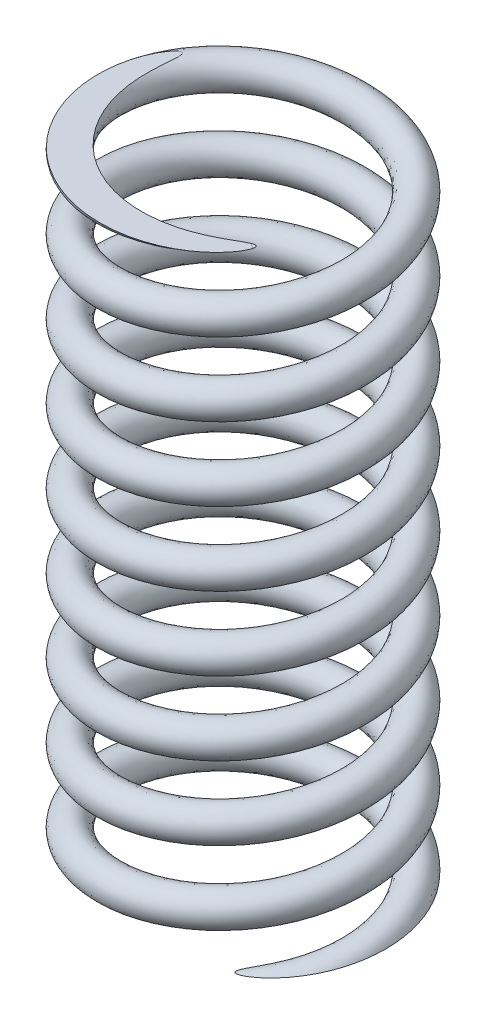
SolidWorks part; units mm, degrees
ref_plane "Front Plane" through (0, 0, 0) normal (0, 0, 1) x (1, 0, 0)
ref_plane "Top Plane" through (0, 0, 0) normal (0, 1, 0) x (1, 0, 0)
ref_plane "Right Plane" through (0, 0, 0) normal (1, 0, 0) x (0, 0, -1)
sketch "Sketch1" plane through (0, 0, 0) normal (0, 1, 0) x (1, 0, 0)
  circle A0 centre (0, 0) radius 14.3
  point P3 (0, 0)
curve "Helix/Spiral3" pitch 8.5703 height 83.56 turns 9.75
sketch "Sketch3" plane through (0, 0, 0) normal (0, 0, 1) x (1, 0, 0)
  circle A0 centre (-14.3, 0) radius 1.95
sweep "Sweep2" add profiles "Sketch3" path "Helix/Spiral3"
ref_plane "Plane4" through (0, 78.5, 0) normal (0, 1, 0) x (1, 0, 0)
other "SurfaceCut2"
ref_plane "Plane6" through (0, 5.1, 0) normal (0, 1, 0) x (1, 0, 0)
other "SurfaceCut3"
